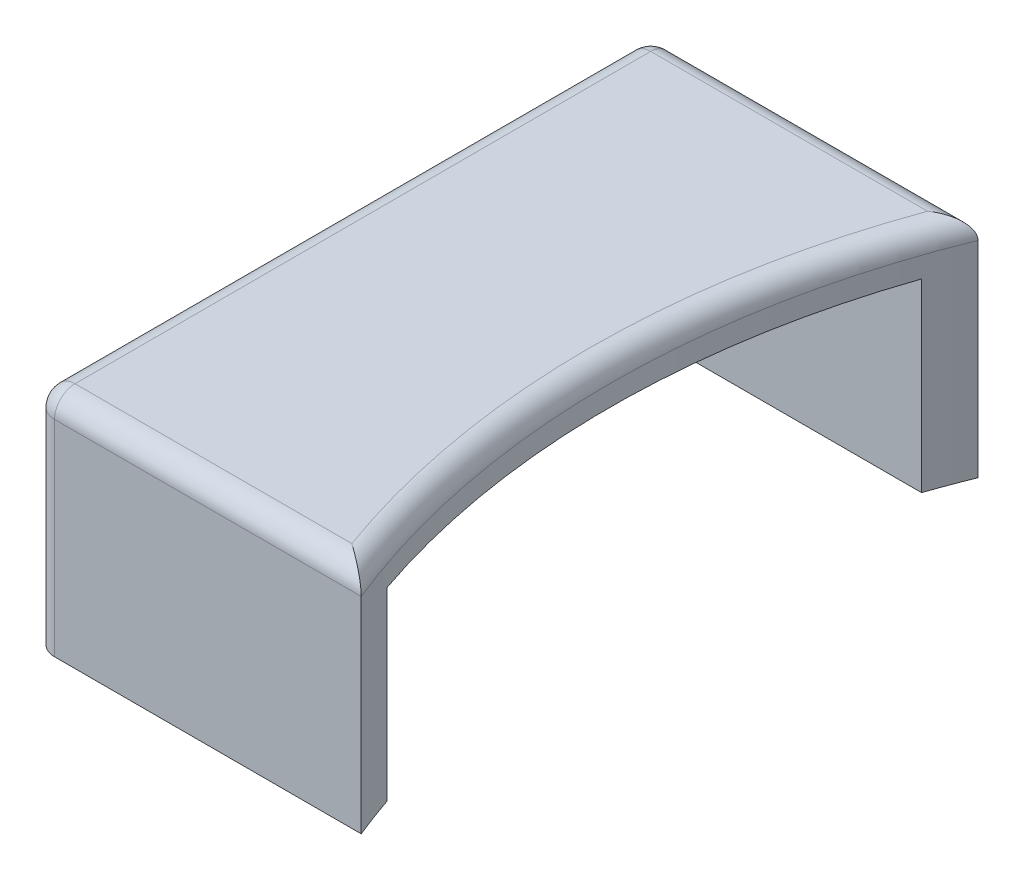
SolidWorks part; units mm, degrees
ref_plane "Front Plane" through (0, 0, 0) normal (0, 0, 1) x (1, 0, 0)
ref_plane "Top Plane" through (0, 0, 0) normal (0, 1, 0) x (1, 0, 0)
ref_plane "Right Plane" through (0, 0, 0) normal (1, 0, 0) x (0, 0, -1)
sketch "Sketch1" plane through (0, 0, 0) normal (0, 1, 0) x (1, 0, 0)
  line L0 (0, 0) -> (0, 30)
  line L2 (0, 0) -> (15.92, 0)
  line L3 (15.92, 30) -> (0, 30)
  line L5 (13, 15) -> (13.0009, 15) construction
  arc A0 (15.92, 30) -> (15.92, 0) centre (53, 15) ccw
  dimension "D1" = 15.92
  dimension "D2" = 30
  dimension "D3" = 15.92
extrude "Boss-Extrude1" add sketch "Sketch1" along normal blind 11
shell "Shell1" thickness 2
fillet "Fillet1" radius 1 6 edges at (13.0009, 11, -15) (0, 5.5, 0) (0, 5.5, -30) (0, 11, -15) (7.96, 11, 0) (7.96, 11, -30)
